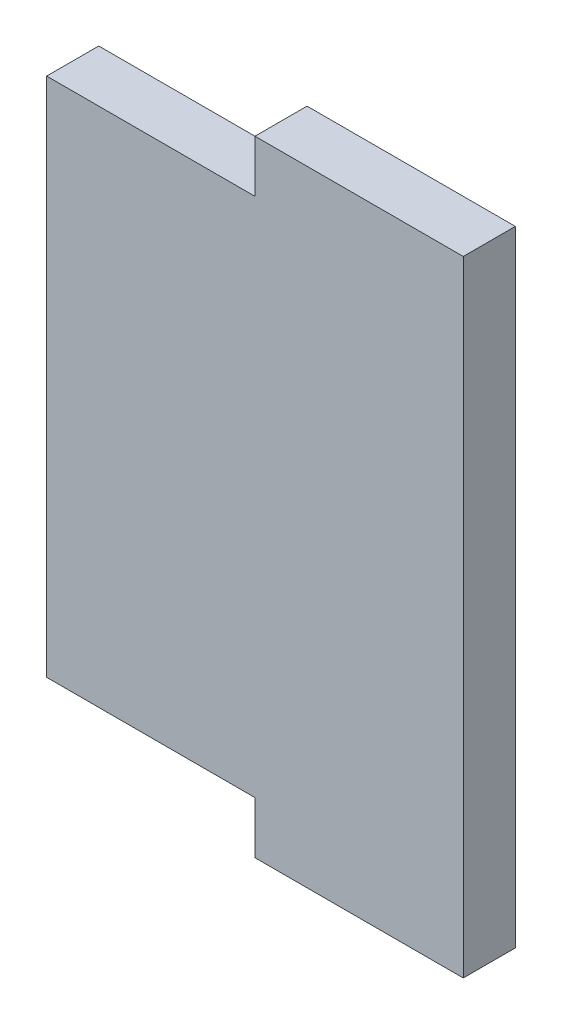
SolidWorks part; units mm, degrees
ref_plane "Front Plane" through (0, 0, 0) normal (0, 0, 1) x (1, 0, 0)
ref_plane "Top Plane" through (0, 0, 0) normal (0, 1, 0) x (1, 0, 0)
ref_plane "Right Plane" through (0, 0, 0) normal (1, 0, 0) x (0, 0, -1)
sketch "Sketch1" plane through (0, 0, 0) normal (0, 0, 1) x (1, 0, 0)
  line L0 (149.225, -34.925) -> (161.925, -34.925) construction
  line L1 (174.625, 0) -> (161.925, 0)
  line L2 (174.625, 0) -> (174.625, -38.1)
  line L3 (174.625, -38.1) -> (161.925, -38.1)
  line L4 (149.225, -3.175) -> (149.225, -34.925)
  line L7 (149.225, -3.175) -> (161.925, -3.175)
  line L8 (161.925, 0) -> (161.925, -3.175)
  line L11 (149.225, -34.925) -> (161.925, -34.925)
  line L12 (161.925, -38.1) -> (161.925, -34.925)
  line L13 (161.925, -38.1) -> (161.925, -34.925) construction
extrude "Boss-Extrude1" add sketch "Sketch1" along normal blind 3.175 contours L2 L3 L12 L11 L4 L7 L8 L1
